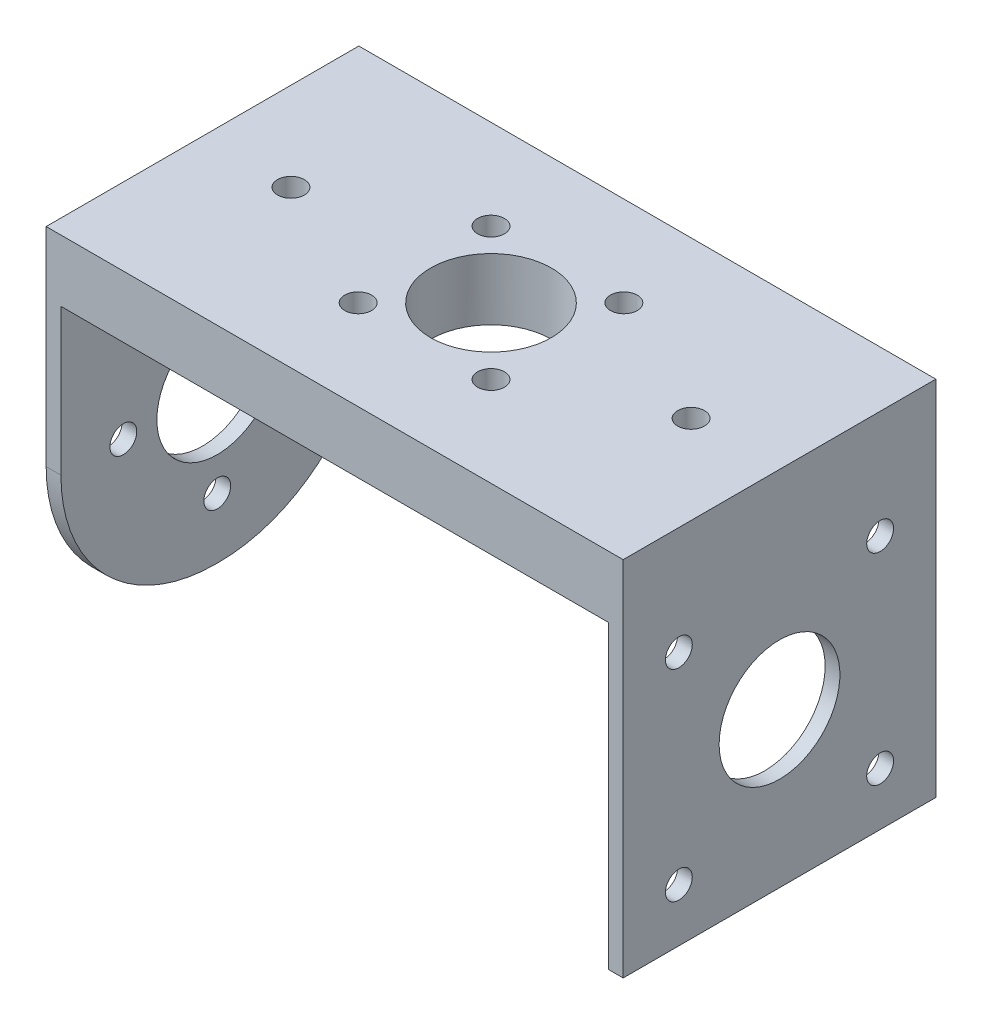
SolidWorks part; units mm, degrees
ref_plane "Front Plane" through (0, 0, 0) normal (0, 0, 1) x (1, 0, 0)
ref_plane "Top Plane" through (0, 0, 0) normal (0, 1, 0) x (1, 0, 0)
ref_plane "Right Plane" through (0, 0, 0) normal (1, 0, 0) x (0, 0, -1)
sketch "Sketch1" plane through (0, 0, 0) normal (0, 1, 0) x (1, 0, 0)
  line L1 (0, 0) -> (43, 0)
  line L2 (0, 0) -> (0, 23.3)
  line L3 (0, 23.3) -> (43, 23.3)
  line L4 (43, 0) -> (43, 23.3)
  dimension "D1" = 43
  dimension "D2" = 23.3
extrude "MountPlate" add sketch "Sketch1" along normal blind 4.6
sketch "Sketch3" plane through (0, 4.6, 0) normal (0, 1, 0) x (1, 0, 0)
  line L1 (43, 0) -> (43, 23.3) construction
  line L2 (43, 23.3) -> (0, 23.3) construction
  circle A0 centre (21.5, 11.65) radius 4.5
  point P6 (43, 11.65)
  point P7 (21.5, 23.3)
  dimension "D1" = 9
extrude "AxleHole-Mount" cut sketch "Sketch3" against normal up to surface (4.6 mm away) up to face at (21.5, 0, -11.65)
sketch "Sketch2" plane through (0, 4.6, 0) normal (0, 1, 0) x (1, 0, 0)
  line L0 (0, 23.3) -> (0, 0) construction
  line L3 (0, 0) -> (43, 0) construction
  circle A1 centre (6.59, 11.65) radius 1
  circle A3 centre (16.5503, 6.7003) radius 1
  circle A4 centre (36.41, 11.65) radius 1
  circle A6 centre (21.5, 11.65) radius 4.5 construction
  circle A7 centre (16.5503, 16.5997) radius 1
  circle A8 centre (26.4497, 16.5997) radius 1
  circle A9 centre (26.4497, 6.7003) radius 1
  point P0 (21.5, 11.65)
  point P5 (21.5, 0)
  point P13 (18.7244, 27.3739)
  point P17 (0, 11.65)
  point P25 (21.5, 11.65)
  dimension "D1" = 2
  dimension "D4" = 29.82
  dimension "D7" = 14.91
  dimension "D3" = 7
  dimension "D5" = 4.9497
  dimension "D2" = 4
extrude "MountHoles" cut sketch "Sketch2" against normal up to surface (4.6 mm away) up to face at (21.5, 0, -16.15)
sketch "Sketch4" plane through (0, 0, 0) normal (0, -1, 0) x (1, 0, 0)
  line L0 (43, -23.3) -> (0, -23.3) construction
  line L1 (43, 0) -> (41.9, 0)
  line L2 (43, 0) -> (43, -23.3)
  line L3 (43, -23.3) -> (41.9, -23.3)
  line L4 (41.9, 0) -> (41.9, -23.3)
  line L6 (0, 0) -> (1.1, 0)
  line L7 (0, 0) -> (0, -23.3)
  line L8 (0, -23.3) -> (1.1, -23.3)
  line L9 (1.1, 0) -> (1.1, -23.3)
  dimension "D1" = 1.1
  dimension "D2" = 1.1
extrude "ServoLegs" add sketch "Sketch4" along normal blind 22.4
sketch "Sketch5" plane through (0, 0, 0) normal (-1, 0, 0) x (0, 0, 1)
  line L5 (0, -22.4) -> (-23.3, -22.4) construction
  circle A0 centre (-11.65, -10.9) radius 4.5
  point P2 (-11.65, -22.4)
  dimension "D1" = 9
  dimension "D2" = 11.5
extrude "CenterHoles" cut sketch "Sketch5" against normal up to surface (43 mm away) up to face at (43, -8.9, -11.65)
sketch "Sketch6" plane through (0, 0, 0) normal (-1, 0, 0) x (0, 0, 1)
  line L0 (0, -22.4) -> (-23.3, -22.4) construction
  circle A0 centre (-11.65, -17.9) radius 1
  circle A1 centre (-11.65, -10.9) radius 4.5 construction
  circle A2 centre (-18.65, -10.9) radius 1
  circle A3 centre (-11.65, -3.9) radius 1
  circle A4 centre (-4.65, -10.9) radius 1
  point P5 (-11.65, -22.4)
  point P16 (-11.65, -10.9)
  dimension "D1" = 2
  dimension "D2" = 7
  dimension "D3" = 4
extrude "RotorSide-MountHoles" cut sketch "Sketch6" against normal up to surface (1.1 mm away) up to face at (1.1, -10.9, -7.15)
fillet "Fillet1" radius 11.5 1 edges at (0.55, -22.4, -23.3)
fillet "Fillet2" radius 11.5 1 edges at (0.55, -22.4, 0)
sketch "Sketch7" plane through (43, 0, 0) normal (1, 0, 0) x (0, 0, -1)
  circle A0 centre (19.15, -18.45) radius 1
  circle A1 centre (19.15, -3.45) radius 1
  circle A2 centre (4.15, -3.45) radius 1
  circle A3 centre (4.15, -18.45) radius 1
  circle A4 centre (11.65, -10.9) radius 4.5 construction
  dimension "D1" = 2
  dimension "D2" = 15
  dimension "D3" = 15
  dimension "D4" = 7.5
  dimension "D5" = 7.55
extrude "SliderSide-MountHoles" cut sketch "Sketch7" against normal up to surface (1.1 mm away) up to face at (41.9, -10.9, -16.15)
equation "\"D7@Sketch2\"=\"D4@Sketch2\"/2"
equation "\"D2@Sketch4\"=\"D1@Sketch4\""
equation "\"D1@ServoLegs\"=27-\"D1@MountPlate\""
equation "\"D2@Sketch5\"=7+\"D1@Sketch5\"/2"
equation "\"D4@Sketch7\"=\"D3@Sketch7\"/2"
equation "\"D5@Sketch2\"=\"D3@Sketch2\"/sqr( 2)"
